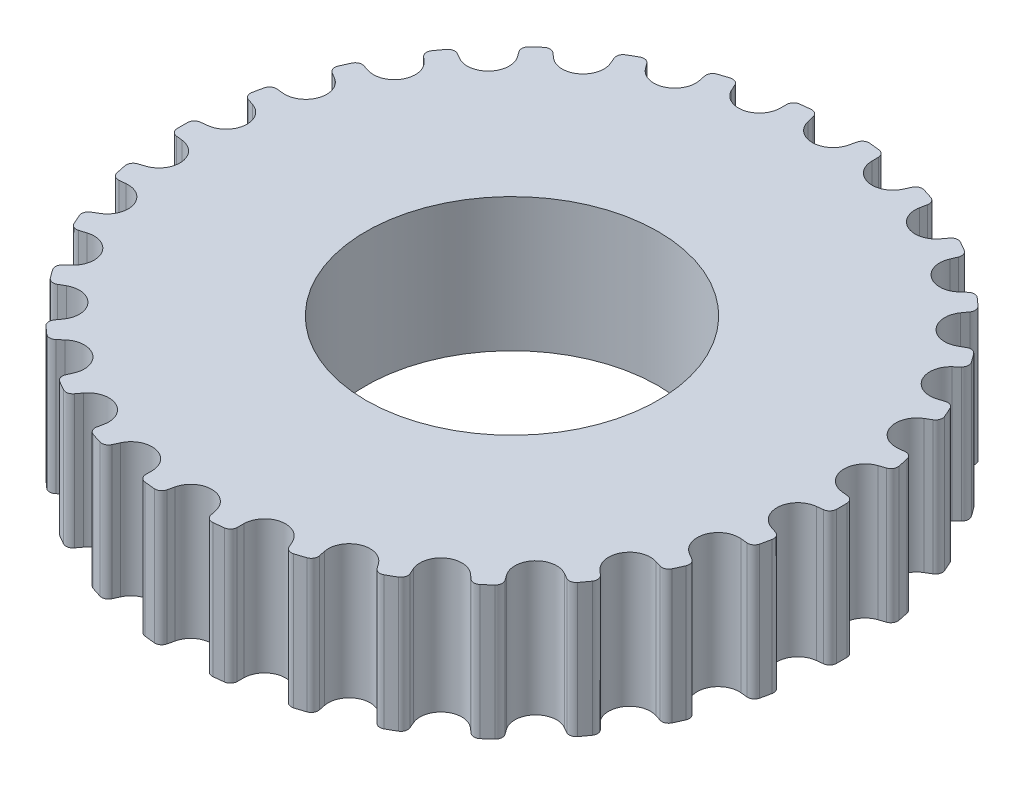
SolidWorks part; units mm, degrees
ref_plane "Front Plane" through (0, 0, 0) normal (0, 0, 1) x (1, 0, 0)
ref_plane "Top Plane" through (0, 0, 0) normal (0, 1, 0) x (1, 0, 0)
ref_plane "Right Plane" through (0, 0, 0) normal (1, 0, 0) x (0, 0, -1)
sketch "Sketch1" plane through (0, 0, 0) normal (0, 1, 0) x (1, 0, 0)
  circle A0 centre (0, 0) radius 14.3239
  dimension "D1" = 28.6479
extrude "Boss-Extrude1" add sketch "Sketch1" along normal blind 5.8
sketch "Sketch2" plane through (0, 5.8, 0) normal (0, 1, 0) x (1, 0, 0)
  line L0 (0, 0) -> (0, 14.3239) construction
  line L1 (-0.8883, 13.7564) -> (-0.95, 14.0339)
  line L2 (-2.9781, 14.0109) -> (-2.9781, 14.3239)
  line L3 (-2.9781, 14.3239) -> (2.9781, 14.3239)
  line L4 (0.8883, 13.7564) -> (0.95, 14.0339)
  line L5 (2.9781, 14.0109) -> (2.9781, 14.3239)
  circle A0 centre (0, 0) radius 14.3239 construction
  arc A1 (0.8883, 13.7564) -> (-0.8883, 13.7564) centre (0, 13.9539) cw
  arc A2 (-0.95, 14.0339) -> (-1.2694, 14.2676) centre (-1.2428, 13.9688) ccw
  arc A4 (0.95, 14.0339) -> (1.2694, 14.2676) centre (1.2428, 13.9688) cw
  arc A5 (-1.2694, 14.2676) -> (-2.9781, 14.0109) centre (0, 0) ccw
  arc A6 (1.2694, 14.2676) -> (2.9781, 14.0109) centre (0, 0) cw
  circle A8 centre (0, 0) radius 14.3239 construction
  point P11 (0, 14.3239)
  point P12 (1.5228, 13.8595)
  point P19 (0, 13.0439)
  point P23 (0, 14.3239)
  point P25 (0, 0)
  dimension "D3" = 0.3
  dimension "D5" = 0.91
  dimension "D2" = 0.95
  dimension "D4" = 1.28
  dimension "D6" = 12
extrude "Cut-Extrude1" cut sketch "Sketch2" against normal through all
pattern_circular "CirPattern1" count 30 over 360 about axis through (0, 0, 0) along (0, 1, 0) of "Cut-Extrude1"
sketch "Sketch3" plane through (0, 0, 0) normal (0, -1, 0) x (1, 0, 0)
  circle A0 centre (0, 0) radius 6.35
  dimension "D1" = 12.7
extrude "Cut-Extrude2" cut sketch "Sketch3" against normal through all
equation "\"smallPulleyTeeth\"= 15"
equation "\"largePulleyTeeth\"= 30"
equation "\"eighthThick\"= 2.9mm"
equation "\"bushingDiam\"= 7.85mm"
equation "\"D1@Sketch1\"=3*\"largePulleyTeeth\"/pi"
equation "\"D1@Boss-Extrude1\" = \"eighthThick\" * 2"
equation "\"D6@Sketch2\"=360/\"largePulleyTeeth\""
equation "\"quarterThick\"=5.6mm"
equation "\"D1@CirPattern1\"=\"largePulleyTeeth\""
